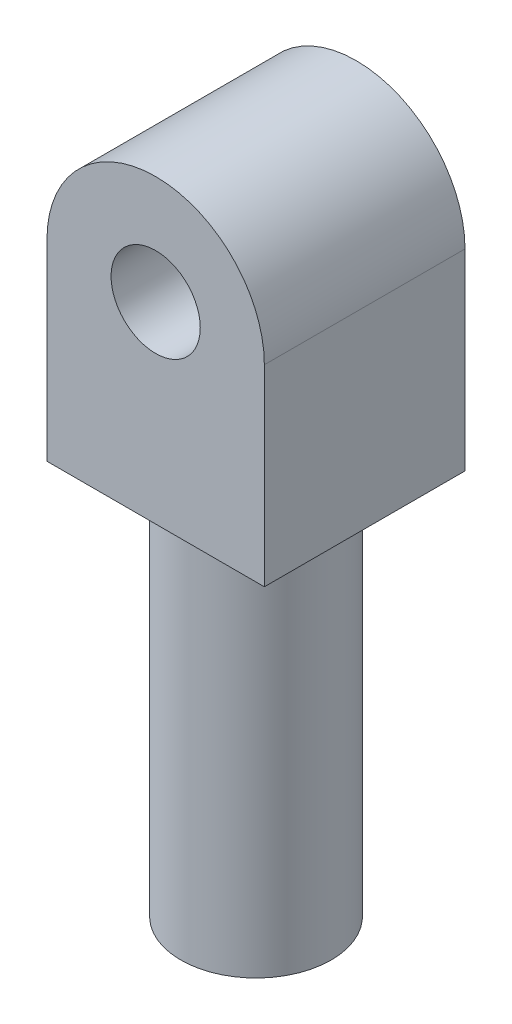
SolidWorks part; units mm, degrees
ref_plane "Front Plane" through (0, 0, 0) normal (0, 0, 1) x (1, 0, 0)
ref_plane "Top Plane" through (0, 0, 0) normal (0, 1, 0) x (1, 0, 0)
ref_plane "Right Plane" through (0, 0, 0) normal (1, 0, 0) x (0, 0, -1)
sketch "Sketch1" plane through (0, 0, 0) normal (0, 0, 1) x (1, 0, 0)
  line L2 (-9.75, 0) -> (-9.75, -17.25)
  line L3 (-9.75, -17.25) -> (9.75, -17.25)
  line L4 (9.75, 0) -> (9.75, -17.25)
  arc A0 (9.75, 0) -> (-9.75, 0) centre (0, 0) ccw
  circle A1 centre (0, 0) radius 4
  point P1 (0, 9.75)
  dimension "D1" = 19.5
  dimension "D2" = 27
  dimension "D3" = 8
extrude "Boss-Extrude2" add sketch "Sketch1" along normal blind 18
sketch "Sketch2" plane through (0, -17.25, 0) normal (0, -1, 0) x (1, 0, 0)
  line L0 (0, 0) -> (0, 18) construction
  line L1 (-9.75, 18) -> (9.75, 18) construction
  circle A0 centre (0, 9) radius 6.75
  dimension "D1" = 13.5
extrude "Boss-Extrude3" add sketch "Sketch2" along normal blind 35
